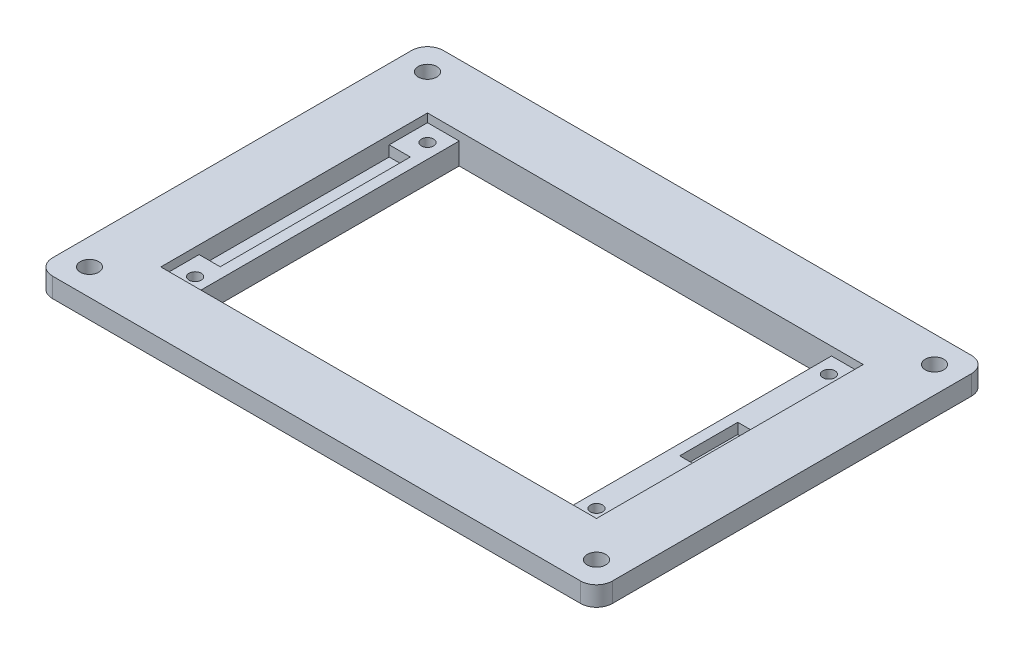
SolidWorks part; units mm, degrees
ref_plane "Спереди" through (0, 0, 0) normal (0, 0, 1) x (1, 0, 0)
ref_plane "Сверху" through (0, 0, 0) normal (0, 1, 0) x (1, 0, 0)
ref_plane "Справа" through (0, 0, 0) normal (1, 0, 0) x (0, 0, -1)
sketch "Эскиз1" plane through (0, 0, 0) normal (0, 1, 0) x (1, 0, 0)
  line L1 (0, 0) -> (106, 0)
  line L2 (0, 0) -> (0, 74)
  line L3 (0, 74) -> (106, 74)
  line L4 (106, 0) -> (106, 74)
  dimension "D1" = 74
  dimension "D2" = 106
extrude "Бобышка-Вытянуть1" add sketch "Эскиз1" along normal blind 5.7
sketch "Эскиз2" plane through (0, 5.7, 0) normal (0, 1, 0) x (1, 0, 0)
  line L0 (17.75, 62.25) -> (0, 62.25) construction
  line L1 (17.75, 11.75) -> (88.25, 11.75)
  line L2 (17.75, 11.75) -> (17.75, 62.25)
  line L3 (17.75, 62.25) -> (88.25, 62.25)
  line L4 (88.25, 11.75) -> (88.25, 62.25)
  line L5 (0, 74) -> (0, 0) construction
  line L6 (88.25, 62.25) -> (106, 62.25) construction
  line L7 (106, 0) -> (106, 74) construction
  line L8 (17.75, 62.25) -> (17.75, 74) construction
  line L9 (106, 74) -> (0, 74) construction
  line L10 (17.75, 11.75) -> (17.75, 0) construction
  line L11 (0, 0) -> (106, 0) construction
  dimension "D1" = 50.5
  dimension "D2" = 70.5
extrude "Вырез-Вытянуть1" cut sketch "Эскиз2" against normal through all
sketch "Эскиз3" plane through (0, 5.7, 0) normal (0, 1, 0) x (1, 0, 0)
  line L0 (11.75, 62.25) -> (0, 62.25) construction
  line L1 (11.75, 11.75) -> (94.25, 11.75)
  line L2 (11.75, 11.75) -> (11.75, 62.25)
  line L3 (11.75, 62.25) -> (94.25, 62.25)
  line L4 (94.25, 11.75) -> (94.25, 62.25)
  line L5 (0, 74) -> (0, 0) construction
  line L6 (94.25, 62.25) -> (106, 62.25) construction
  line L7 (106, 0) -> (106, 74) construction
  line L8 (11.75, 62.25) -> (11.75, 74) construction
  line L9 (106, 74) -> (0, 74) construction
  line L10 (11.75, 11.75) -> (11.75, 0) construction
  line L11 (0, 0) -> (106, 0) construction
  dimension "D1" = 82.5
  dimension "D2" = 50.5
extrude "Вырез-Вытянуть2" cut sketch "Эскиз3" against normal blind 1.6
sketch "Эскиз4" plane through (0, 4.1, 0) normal (0, 1, 0) x (1, 0, 0)
  line L0 (94.25, 11.75) -> (94.25, 62.25) construction
  line L1 (94.25, 31.5) -> (90.25, 31.5)
  line L2 (94.25, 31.5) -> (94.25, 42.5)
  line L3 (94.25, 42.5) -> (90.25, 42.5)
  line L4 (90.25, 31.5) -> (90.25, 42.5)
  line L5 (92.25, 42.5) -> (92.25, 62.25) construction
  line L6 (94.25, 62.25) -> (11.75, 62.25) construction
  line L7 (92.25, 31.5) -> (92.25, 11.75) construction
  line L8 (11.75, 11.75) -> (94.25, 11.75) construction
  line L9 (11.75, 62.25) -> (11.75, 11.75) construction
  line L10 (11.75, 19) -> (15.75, 19)
  line L11 (11.75, 19) -> (11.75, 55)
  line L12 (11.75, 55) -> (15.75, 55)
  line L13 (15.75, 19) -> (15.75, 55)
  line L14 (13.75, 55) -> (13.75, 62.25) construction
  line L15 (13.75, 19) -> (13.75, 11.75) construction
  dimension "D1" = 4
  dimension "D2" = 11
  dimension "D3" = 4
  dimension "D4" = 36
extrude "Вырез-Вытянуть3" cut sketch "Эскиз4" against normal blind 2
sketch "Эскиз5" plane through (0, 4.1, 0) normal (0, 1, 0) x (1, 0, 0)
  line L0 (14.531, 59) -> (14.531, 62.25) construction
  line L1 (15, 15) -> (91, 15) construction
  line L2 (15, 15) -> (15, 59) construction
  line L3 (15, 59) -> (91, 59) construction
  line L4 (91, 15) -> (91, 59) construction
  line L5 (94.25, 62.25) -> (11.75, 62.25) construction
  line L6 (14.531, 15) -> (14.531, 11.75) construction
  line L7 (11.75, 11.75) -> (94.25, 11.75) construction
  line L8 (15, 51.0481) -> (11.75, 51.0481) construction
  line L9 (11.75, 62.25) -> (11.75, 55) construction
  line L10 (91, 51.0481) -> (94.25, 51.0481) construction
  line L11 (94.25, 42.5) -> (94.25, 62.25) construction
  circle A0 centre (15, 59) radius 1.15
  circle A1 centre (91, 59) radius 1.15
  circle A2 centre (91, 15) radius 1.15
  circle A3 centre (15, 15) radius 1.15
  dimension "D3" = 2.3
  dimension "D1" = 76
  dimension "D2" = 44
extrude "Вырез-Вытянуть4" cut sketch "Эскиз5" against normal blind 3.9
sketch "Эскиз6" plane through (0, 5.7, 0) normal (0, 1, 0) x (1, 0, 0)
  line L0 (17.75, 62.25) -> (17.75, 65.25) construction
  line L5 (-11.5023, -4.6392) -> (119.6328, -4.6392)
  line L6 (-11.5023, -4.6392) -> (-11.5023, 83.9209)
  line L7 (-11.5023, 83.9209) -> (119.6328, 83.9209)
  line L8 (119.6328, -4.6392) -> (119.6328, 83.9209)
  line L9 (8.75, 8.75) -> (97.25, 8.75)
  line L10 (8.75, 8.75) -> (8.75, 65.25)
  line L11 (8.75, 65.25) -> (97.25, 65.25)
  line L12 (97.25, 8.75) -> (97.25, 65.25)
  line L13 (17.75, 11.75) -> (17.75, 8.75) construction
  line L14 (8.75, 52.6247) -> (17.75, 52.6247) construction
  line L15 (17.75, 62.25) -> (17.75, 11.75) construction
  line L16 (97.25, 51.9037) -> (88.25, 51.9037) construction
  line L17 (88.25, 11.75) -> (88.25, 62.25) construction
  point P24 (119.6328, 83.9209)
  dimension "D1" = 56.5
  dimension "D2" = 88.5
extrude "Вырез-Вытянуть5" cut sketch "Эскиз6" along normal blind 2 from surface at -5.7 starting at face at (53, 0, -37)
sketch "Эскиз7" plane through (0, 2, 0) normal (0, -1, 0) x (1, 0, 0)
  line L0 (12.5342, -5) -> (12.5342, 0) construction
  line L1 (5, -69) -> (101, -69) construction
  line L2 (5, -69) -> (5, -5) construction
  line L3 (5, -5) -> (101, -5) construction
  line L4 (101, -69) -> (101, -5) construction
  line L5 (106, 0) -> (0, 0) construction
  line L6 (12.5342, -69) -> (12.5342, -74) construction
  line L7 (0, -74) -> (106, -74) construction
  line L8 (5, -65.3432) -> (0, -65.3432) construction
  line L9 (0, 0) -> (0, -74) construction
  line L10 (101, -65.3432) -> (106, -65.3432) construction
  line L11 (106, -74) -> (106, 0) construction
  circle A0 centre (5, -5) radius 1.75
  circle A1 centre (101, -5) radius 1.75
  circle A2 centre (101, -69) radius 1.75
  circle A3 centre (5, -69) radius 1.75
  dimension "D1" = 3.5
  dimension "D2" = 64
  dimension "D3" = 96
extrude "Вырез-Вытянуть6" cut sketch "Эскиз7" against normal through all
fillet "Скругление1" radius 3 4 edges at (0, 3.85, -74) (106, 3.85, -74) (106, 3.85, 0) (0, 3.85, 0)
